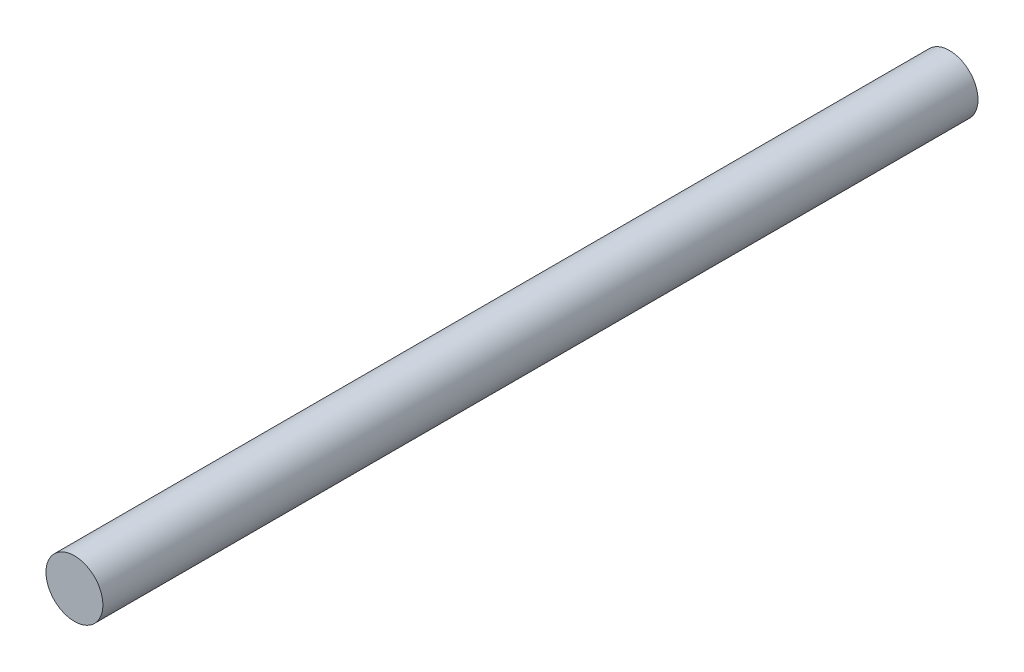
SolidWorks part; units mm, degrees
ref_plane "Alzado" through (0, 0, 0) normal (0, 0, 1) x (1, 0, 0)
ref_plane "Planta" through (0, 0, 0) normal (0, 1, 0) x (1, 0, 0)
ref_plane "Vista lateral" through (0, 0, 0) normal (1, 0, 0) x (0, 0, -1)
sketch "Croquis1" plane through (0, 0, 0) normal (0, 0, 1) x (1, 0, 0)
  circle A0 centre (0, 0) radius 7.5
  point P4 (0, 0)
  dimension "D1" = 15
extrude "Saliente-Extruir1" add sketch "Croquis1" along normal blind 230.51
